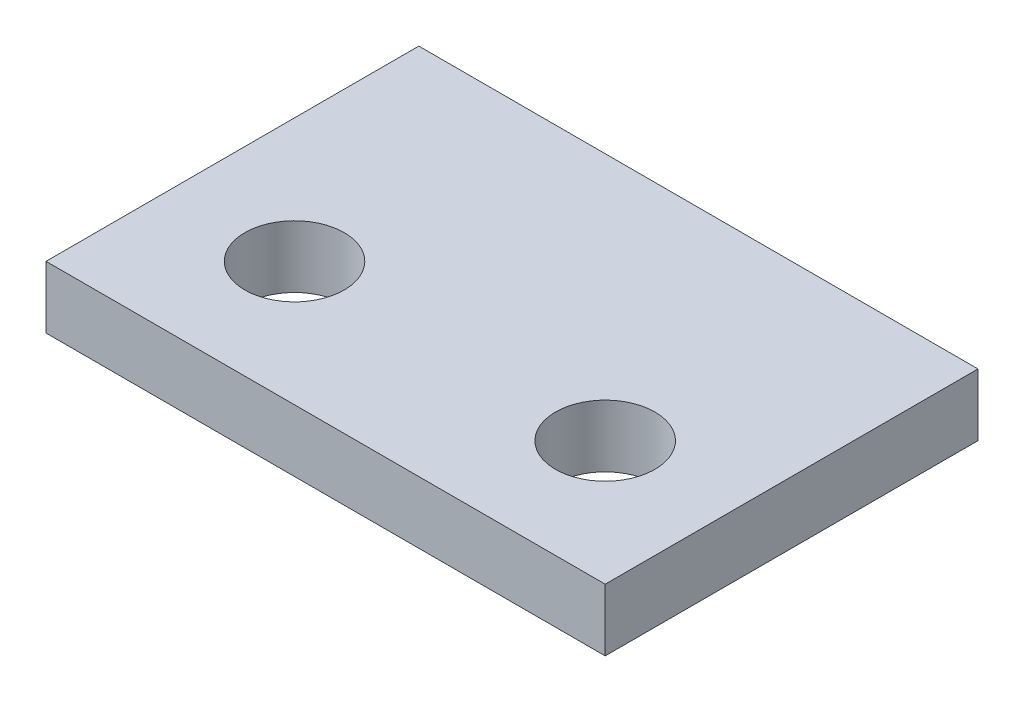
SolidWorks part; units mm, degrees
ref_plane "前视基准面" through (0, 0, 0) normal (0, 0, 1) x (1, 0, 0)
ref_plane "上视基准面" through (0, 0, 0) normal (0, 1, 0) x (1, 0, 0)
ref_plane "右视基准面" through (0, 0, 0) normal (1, 0, 0) x (0, 0, -1)
sketch "草图1" plane through (0, 0, 0) normal (0, 1, 0) x (1, 0, 0)
  line L0 (0, 257.0131) -> (0, -257.0131) construction
  line L1 (-257.0131, 0) -> (257.0131, 0) construction
  line L2 (9, -4) -> (-9, -4)
  line L3 (-9, -4) -> (-9, 8)
  line L4 (-9, 8) -> (9, 8)
  line L5 (9, -4) -> (9, 8)
  circle A0 centre (-5, 0) radius 1.6
  circle A1 centre (5, 0) radius 1.6
  point P14 (0, -4)
  point P15 (0, 8)
  dimension "D1" = 10
  dimension "D2" = 3.2
  dimension "D3" = 4
  dimension "D4" = 4
  dimension "D5" = 8
extrude "凸台-拉伸1" add sketch "草图1" along normal blind 2
